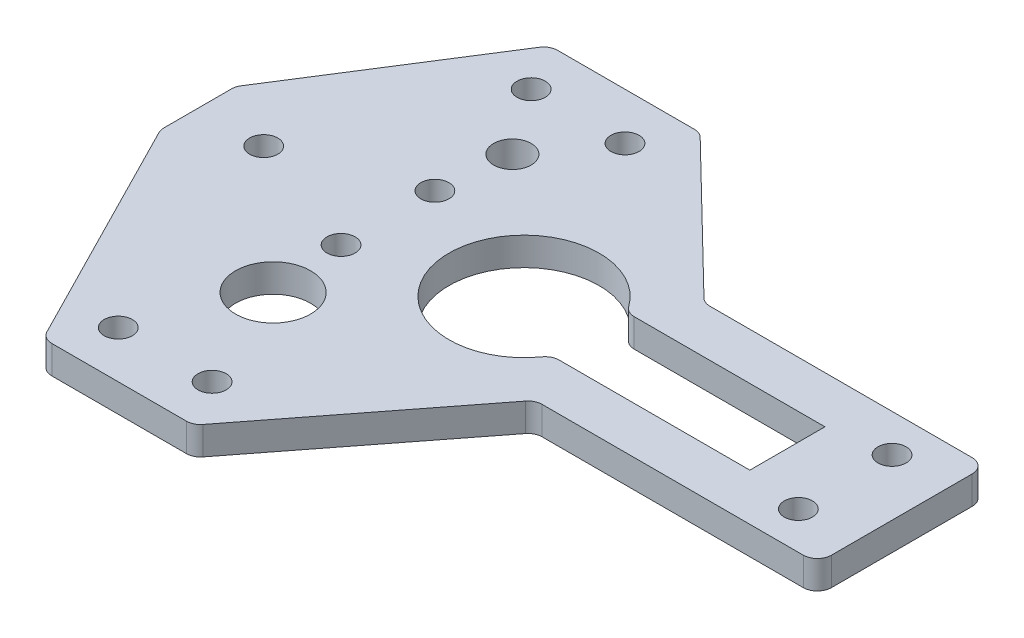
SolidWorks part; units mm, degrees
ref_plane "Plan de face" through (0, 0, 0) normal (0, 0, 1) x (1, 0, 0)
ref_plane "Plan de dessus" through (0, 0, 0) normal (0, 1, 0) x (1, 0, 0)
ref_plane "Plan de droite" through (0, 0, 0) normal (1, 0, 0) x (0, 0, -1)
ref_plane "Plan1" through (0, 3, 0) normal (0, 1, 0) x (1, 0, 0)
sketch "Esquisse1" plane through (0, 3, 0) normal (0, 1, 0) x (1, 0, 0)
  line L0 (-26.75, -5) -> (-26.75, 5)
  line L1 (-24.25, 7.5) -> (-21.75, 7.5)
  line L2 (-19.25, 5) -> (-19.25, -5)
  line L3 (-21.75, -7.5) -> (-24.25, -7.5)
  line L4 (27.25, 2.5) -> (27.25, -2.5)
  line L5 (25.75, -4) -> (7.746, -4)
  line L6 (7.746, 4) -> (25.75, 4)
  line L7 (-24.4418, 23.8033) -> (-36.7668, 4.3678)
  line L8 (-37, 3.5645) -> (-37, -3.6397)
  line L9 (-36.8364, -4.321) -> (-24.4174, -28.6813)
  line L10 (-23.081, -29.5) -> (-8.7341, -29.5)
  line L11 (-7.5496, -28.9203) -> (7.4778, -9.5797)
  line L12 (8.6623, -9) -> (36.5, -9)
  line L13 (38, -7.5) -> (38, 7.5)
  line L14 (36.5, 9) -> (8.5376, 9)
  line L15 (7.4915, 9.425) -> (-7.5633, 24.075)
  line L16 (-8.6094, 24.5) -> (-23.175, 24.5)
  circle A0 centre (33, -5) radius 1.5
  circle A1 centre (-16, 12.5) radius 2
  arc A2 (-26.75, 5) -> (-24.25, 7.5) centre (-24.25, 5) cw
  arc A3 (-21.75, 7.5) -> (-19.25, 5) centre (-21.75, 5) cw
  arc A4 (-19.25, -5) -> (-21.75, -7.5) centre (-21.75, -5) cw
  arc A5 (-24.25, -7.5) -> (-26.75, -5) centre (-24.25, -5) cw
  circle A6 centre (-21, -24.5) radius 1.5
  circle A7 centre (-21, 19.5) radius 1.5
  circle A8 centre (-16, -5) radius 1.5
  arc A9 (27.25, -2.5) -> (25.75, -4) centre (25.75, -2.5) cw
  arc A10 (7.746, -4) -> (6.5229, -4.6316) centre (7.746, -5.5) ccw
  arc A11 (6.5229, -4.6316) -> (6.5229, 4.6316) centre (0, 0) cw
  arc A12 (6.5229, 4.6316) -> (7.746, 4) centre (7.746, 5.5) ccw
  arc A13 (25.75, 4) -> (27.25, 2.5) centre (25.75, 2.5) cw
  arc A14 (-36.7668, 4.3678) -> (-37, 3.5645) centre (-35.5, 3.5645) ccw
  arc A15 (-37, -3.6397) -> (-36.8364, -4.321) centre (-35.5, -3.6397) ccw
  arc A16 (-24.4174, -28.6813) -> (-23.081, -29.5) centre (-23.081, -28) ccw
  arc A17 (-8.7341, -29.5) -> (-7.5496, -28.9203) centre (-8.7341, -28) ccw
  arc A18 (7.4778, -9.5797) -> (8.6623, -9) centre (8.6623, -10.5) cw
  arc A19 (36.5, -9) -> (38, -7.5) centre (36.5, -7.5) ccw
  arc A20 (38, 7.5) -> (36.5, 9) centre (36.5, 7.5) ccw
  arc A21 (8.5376, 9) -> (7.4915, 9.425) centre (8.5376, 10.5) cw
  arc A22 (-7.5633, 24.075) -> (-8.6094, 24.5) centre (-8.6094, 23) ccw
  arc A23 (-23.175, 24.5) -> (-24.4418, 23.8033) centre (-23.175, 23) ccw
  circle A24 centre (-16, 5) radius 1.5
  circle A25 centre (-11, 19.5) radius 1.5
  circle A26 centre (-11, -24.5) radius 1.5
  circle A27 centre (-32, 0) radius 1.5
  circle A28 centre (-16, -13) radius 4
  circle A29 centre (33, 5) radius 1.5
  dimension "D1" = 19.504
extrude "Boss.-Extru.1" add sketch "Esquisse1" against normal blind 3
sketch "Esquisse4" plane through (0, 3, 0) normal (0, 1, 0) x (1, 0, 0)
  line L5 (-8.4288, 5.3104) -> (-10.2835, 5.3104)
  line L6 (-27.5232, 8.8081) -> (-18.0856, 8.8081)
  line L7 (-27.5232, 8.8081) -> (-27.5232, -8.8919)
  line L8 (-27.5232, -8.8919) -> (-18.0856, -8.8919)
  line L9 (-18.0856, 8.8081) -> (-18.0856, -8.8919)
  line L10 (29.3576, 5.3104) -> (8.4288, 5.3104)
  line L11 (29.3576, 5.3104) -> (29.3576, -6.1885)
  line L12 (29.3576, -6.1885) -> (7.8069, -6.1885)
  line L13 (-10.2835, 5.3104) -> (-10.2835, -6.1885)
  line L14 (-7.8069, -6.1885) -> (-10.2835, -6.1885)
  circle A0 centre (-32, 0) radius 2.5632
  arc A1 (-7.8069, -6.1885) -> (7.8069, -6.1885) centre (0, 0) ccw
  arc A2 (8.4288, 5.3104) -> (-8.4288, 5.3104) centre (0, 0) ccw
extrude "Boss.-Extru.3" add sketch "Esquisse4" against normal blind 3
sketch "Esquisse5" plane through (0, 3, 0) normal (0, 1, 0) x (1, 0, 0)
  line L0 (-44.5162, 0) -> (43.8781, 0) construction
  line L1 (36.5, 9) -> (8.5376, 9) construction
  line L2 (5.4858, 4) -> (25.8058, 4)
  line L4 (5.4858, -4) -> (25.8058, -4)
  line L5 (25.8058, 4) -> (25.8058, -4)
  line L6 (-15.8922, 30.436) -> (-15.8922, -30.5077) construction
  line L7 (-37, 3.5645) -> (-37, -3.6397) construction
  circle A0 centre (-30, 0) radius 1.5
  arc A1 (4.2628, 4.6316) -> (4.2628, -4.6316) centre (-2.2602, 0) ccw
  arc A2 (4.2628, 4.6316) -> (5.4858, 4) centre (5.4858, 5.5) ccw
  arc A3 (5.4858, -4) -> (4.2628, -4.6316) centre (5.4858, -5.5) ccw
  point P12 (0, 0)
  point P20 (-5, 0)
  point P21 (0, 0)
  point P22 (0, 0)
  point P23 (0, 0)
  dimension "D1" = 9
  dimension "D4" = 3
  dimension "D6" = 8
  dimension "D2" = 8
  dimension "D3" = 20.32
  dimension "D5" = 7
extrude "Enlèv. mat.-Extru.1" cut sketch "Esquisse5" against normal blind 10 contours A1 A3 L4 L5 L2 A2 | A0
sketch "Esquisse6" plane through (0, 3, 0) normal (0, 1, 0) x (1, 0, 0)
  line L0 (-16, 5) -> (33, 5) construction
  line L1 (33, 5) -> (33, -5) construction
  line L2 (33, -5) -> (-16, -5) construction
  line L3 (-16, -5) -> (-16, 5) construction
  circle A0 centre (33, 5) radius 1.5
  circle A1 centre (33, -5) radius 1.5
extrude "Boss.-Extru.5" add sketch "Esquisse6" against normal blind 3
sketch "Esquisse7" plane through (0, 3, 0) normal (0, 1, 0) x (1, 0, 0)
  line L0 (-16, 5) -> (31.9755, 4.9847) construction
  line L1 (-16, -5) -> (-16, 5) construction
  line L2 (-16, -5) -> (31.9755, -5) construction
  line L3 (31.9755, -5) -> (31.9755, 4.9847) construction
  circle A0 centre (31.9755, 4.9847) radius 1.5
  circle A1 centre (31.9755, -5) radius 1.5
  point P0 (32.8355, 4.9847)
  dimension "D1" = 0.86
extrude "Enlèv. mat.-Extru.2" cut sketch "Esquisse7" against normal blind 3
sketch "Esquisse8" plane through (0, 3, 0) normal (0, 1, 0) x (1, 0, 0)
  circle A0 centre (-16, 5) radius 1.5
  circle A1 centre (-16, -5) radius 1.5
  circle A2 centre (-16.7594, 5) radius 1.5
  circle A3 centre (-16.7594, -5) radius 1.5
  point P7 (-16, 5)
  circle M7 centre (-16, 5) radius 1.5
  circle M8 centre (-16, -5) radius 1.5
extrude "Enlèv. mat.-Extru.3" cut sketch "Esquisse8" against normal blind 3 contours A2 M7 | A3 M8
sketch "Esquisse10" plane through (0, 3, 0) normal (0, 1, 0) x (1, 0, 0)
  arc A0 (-16.3797, 3.5489) -> (-16.3797, 6.4511) centre (-16.7594, 5) ccw
  arc A1 (-16.3797, 3.5489) -> (-16.3797, 6.4511) centre (-16, 5) ccw
  arc A2 (-16.3797, -6.4511) -> (-16.3797, -3.5489) centre (-16.7594, -5) ccw
  arc A3 (-16.3797, -6.4511) -> (-16.3797, -3.5489) centre (-16, -5) ccw
extrude "Boss.-Extru.7" add sketch "Esquisse10" against normal blind 3
